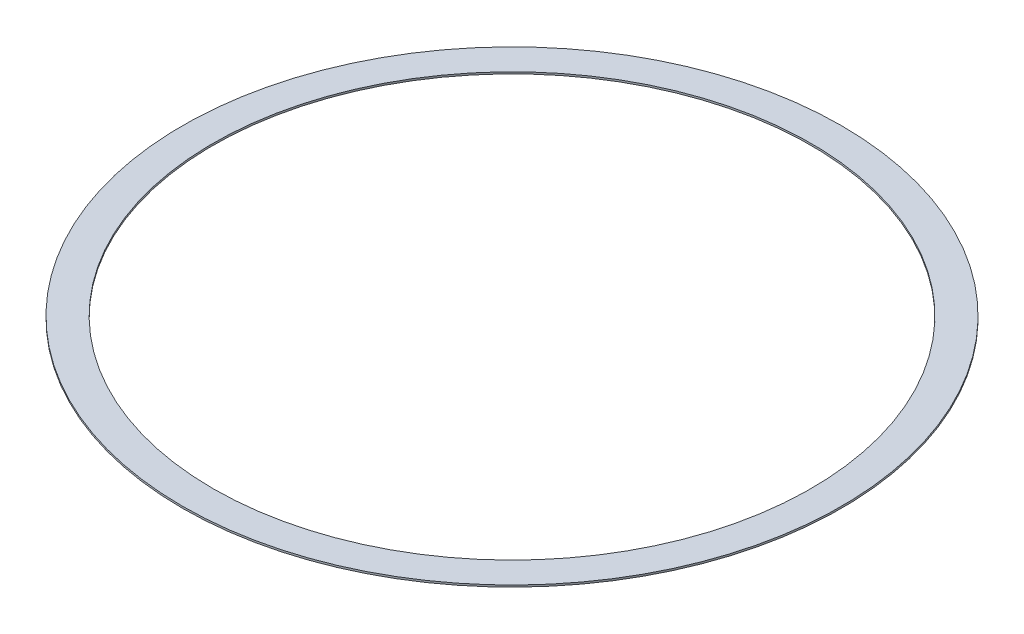
SolidWorks part; units mm, degrees
material "Oak"
ref_plane "Front Plane" through (0, 0, 0) normal (0, 0, 1) x (1, 0, 0)
ref_plane "Top Plane" through (0, 0, 0) normal (0, 1, 0) x (1, 0, 0)
ref_plane "Right Plane" through (0, 0, 0) normal (1, 0, 0) x (0, 0, -1)
sketch "Sketch1" plane through (0, 0, 0) normal (0, 1, 0) x (1, 0, 0)
  circle A0 centre (0, 0) radius 540
  circle A1 centre (0, 0) radius 490
extrude "Boss-Extrude1" add sketch "Sketch1" along normal blind 3
